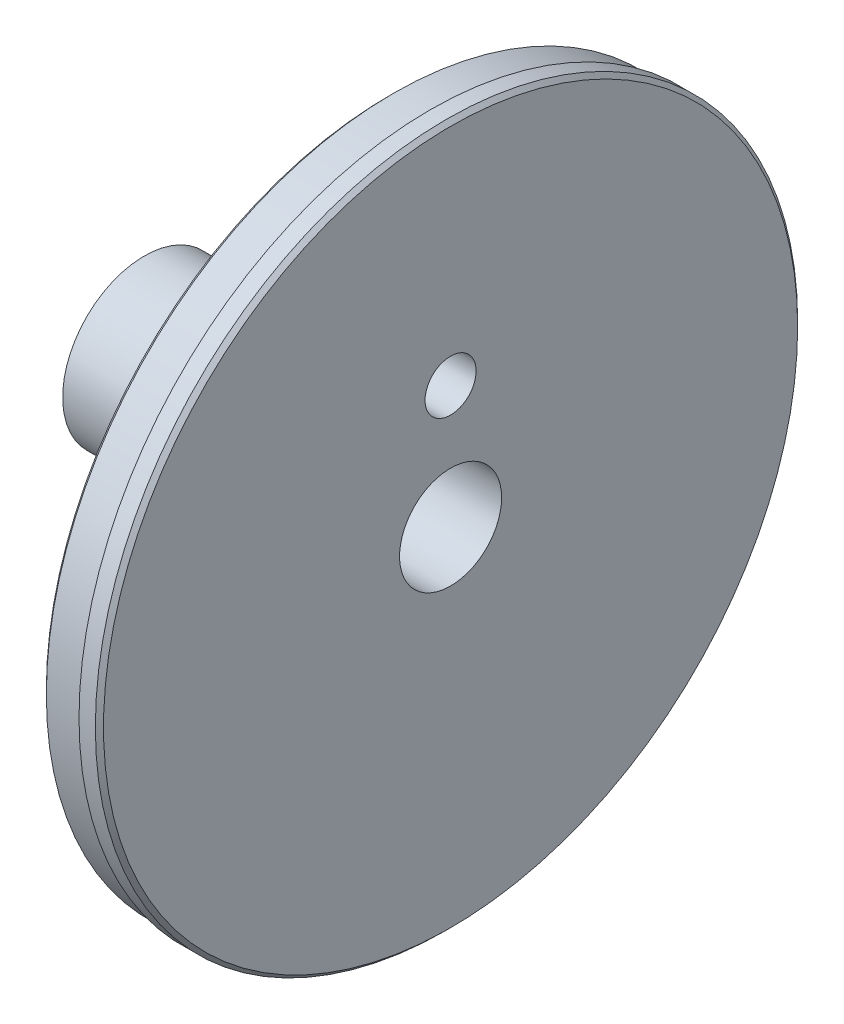
SolidWorks part; units mm, degrees
ref_plane "Front Plane" through (0, 0, 0) normal (0, 0, 1) x (1, 0, 0)
ref_plane "Top Plane" through (0, 0, 0) normal (0, 1, 0) x (1, 0, 0)
ref_plane "Right Plane" through (0, 0, 0) normal (1, 0, 0) x (0, 0, -1)
sketch "Sketch1" plane through (0, 0, 0) normal (0, 0, 1) x (1, 0, 0)
  line L0 (0, 0) -> (-16.767, 0) construction
  line L1 (0, 2.5) -> (0, 17.2)
  line L3 (-3, 17) -> (-3, 9)
  line L4 (-3, 9) -> (-6, 9)
  line L5 (-6, 9) -> (-6, 4)
  line L6 (-6, 4) -> (-15, 4)
  line L7 (-15, 4) -> (-15, 2.5)
  line L8 (-15, 2.5) -> (0, 2.5)
  line L9 (0, 17.2) -> (-1, 17.2)
  line L10 (-1, 17.2) -> (-1, 17)
  line L11 (-1, 17) -> (-3, 17)
  dimension "D1" = 5
  dimension "D2" = 8
  dimension "D3" = 18
  dimension "D4" = 34
  dimension "D5" = 34.4
  dimension "D6" = 1
  dimension "D7" = 3
  dimension "D8" = 6
  dimension "D9" = 15
revolve "Revolve1" add sketch "Sketch1" angle 360 about L0
sketch "Sketch2" plane through (-6, 0, 0) normal (-1, 0, 0) x (0, 0, 1)
  circle A0 centre (0, 6) radius 1.25
  dimension "D1" = 2.5
  dimension "D2" = 6
extrude "Cut-Extrude1" cut sketch "Sketch2" against normal through all
chamfer "Chamfer1" distance 0.2 angle 45 2 edges at (-3, 0, -17) (0, 0, -17.2)
